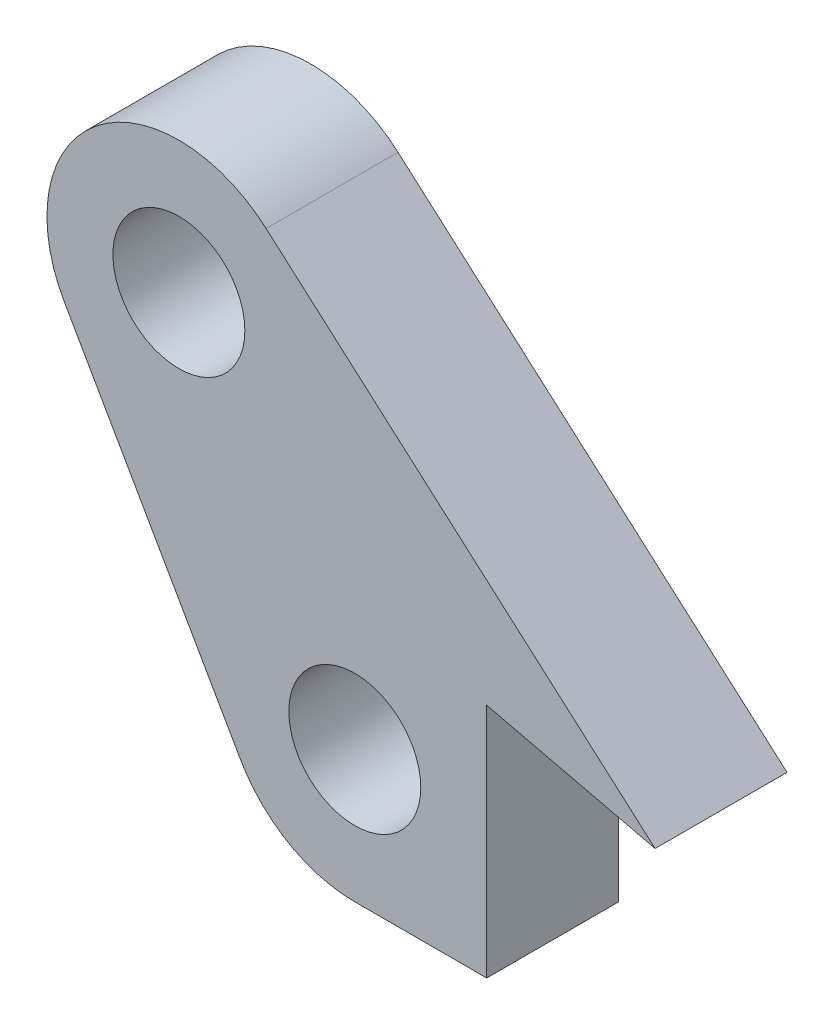
SolidWorks part; units mm, degrees
ref_plane "Спереди" through (0, 0, 0) normal (0, 0, 1) x (1, 0, 0)
ref_plane "Сверху" through (0, 0, 0) normal (0, 1, 0) x (1, 0, 0)
ref_plane "Справа" through (0, 0, 0) normal (1, 0, 0) x (0, 0, -1)
other "Configuration Table"
sketch "Sketch1" plane through (0, 0, 0) normal (0, 0, 1) x (1, 0, 0)
  line L0 (-20.3982, 8.5116) -> (-16.3982, 1.5116)
  line L1 (-10.7935, 5.3717) -> (-6.9655, 4.4638)
  line L2 (-6.9655, 4.4638) -> (-15.811, 12.2517)
  line L6 (-13.7935, 0) -> (-10.7935, 0)
  line L7 (-10.7935, 0) -> (-10.7935, 5.3717)
  arc A0 (-15.811, 12.2517) -> (-20.3982, 8.5116) centre (-17.7935, 10) ccw
  circle A1 centre (-17.7935, 10) radius 1.5
  arc A2 (-16.3982, 1.5116) -> (-13.7935, 0) centre (-13.7935, 3) ccw
  circle A3 centre (-13.7935, 3) radius 1.5
  point P4 (-17.7935, 10)
  dimension "D1" = 3
  dimension "D4" = 6
  dimension "D5" = 3
  dimension "D6" = 3
  dimension "D2" = 7
  dimension "D3" = 4
extrude "Boss-Extrude1" add sketch "Sketch1" along normal blind 3
